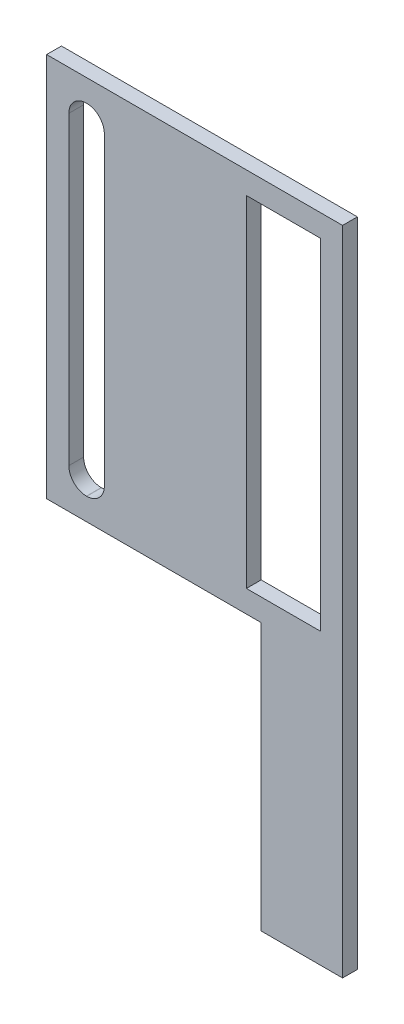
SolidWorks part; units mm, degrees
ref_plane "Front Plane" through (0, 0, 0) normal (0, 0, 1) x (1, 0, 0)
ref_plane "Top Plane" through (0, 0, 0) normal (0, 1, 0) x (1, 0, 0)
ref_plane "Right Plane" through (0, 0, 0) normal (1, 0, 0) x (0, 0, -1)
sketch "Sketch1" plane through (0, 0, 0) normal (0, 0, 1) x (1, 0, 0)
  line L1 (2.75, -19.65) -> (-2.75, -19.65)
  line L2 (2.75, -19.65) -> (2.75, 19.65)
  line L3 (2.75, 19.65) -> (-2.75, 19.65)
  line L4 (-2.75, -19.65) -> (-2.75, 19.65)
  line L5 (2.75, -19.65) -> (-2.75, 19.65) construction
  line L6 (2.75, 19.65) -> (-2.75, -19.65) construction
  point P0 (0, 0)
  dimension "D1" = 39.3
  dimension "D2" = 5.5
extrude "Boss-Extrude1" add sketch "Sketch1" along normal blind 1
sketch "Sketch2" plane through (0, 0, 1) normal (0, 0, 1) x (1, 0, 0)
  line L0 (-2.75, 19.65) -> (-2.75, -19.65) construction
  line L1 (2.75, 19.65) -> (-2.75, 19.65) construction
  line L3 (-0.25, 15.9) -> (-2.75, 15.9)
  line L4 (-0.25, 15.9) -> (-0.25, 12.9)
  line L5 (-0.25, 12.9) -> (-2.75, 12.9)
  line L6 (-2.75, 15.9) -> (-2.75, 12.9)
  line L7 (-0.25, 9.9) -> (-2.75, 9.9)
  line L8 (-0.25, 9.9) -> (-0.25, 6.9)
  line L9 (-0.25, 6.9) -> (-2.75, 6.9)
  line L10 (-2.75, 9.9) -> (-2.75, 6.9)
  circle A0 centre (-0.25, 14.4) radius 1.5
  circle A1 centre (-0.25, 8.4) radius 1.5
  dimension "D1" = 3
  dimension "D5" = 3
  dimension "D2" = 2.5
  dimension "D3" = 5.25
  dimension "D4" = 2.5
  dimension "D6" = 11.25
  dimension "D7" = 3
  dimension "D8" = 3
sketch "Sketch3" plane through (0, 0, 1) normal (0, 0, 1) x (1, 0, 0)
  line L0 (2.75, -19.65) -> (2.75, 19.65) construction
  line L1 (2.75, -1.6) -> (-17.25, -1.6)
  line L2 (2.75, -1.6) -> (2.75, 24.4)
  line L3 (2.75, 24.4) -> (-17.25, 24.4)
  line L4 (-17.25, -1.6) -> (-17.25, 24.4)
  dimension "D1" = 0
  dimension "D2" = 10
  dimension "D3" = 10
  dimension "D4" = 20
extrude "Boss-Extrude5" add sketch "Sketch3" against normal up to surface (1 mm away) up to face at (0, 0, 0)
sketch "Sketch4" plane through (0, 0, 1) normal (0, 0, 1) x (1, 0, 0)
  line L0 (2.75, 24.4) -> (-17.25, 24.4) construction
  line L1 (-14.56, 22.9) -> (-14.54, 22.9)
  line L2 (-15.75, 21.71) -> (-15.75, 1.09)
  line L3 (-14.56, -0.1) -> (-14.54, -0.1)
  line L4 (-13.35, 21.71) -> (-13.35, 1.09)
  line L5 (-17.25, -1.6) -> (-2.75, -1.6) construction
  line L6 (-17.25, 24.4) -> (-17.25, -1.6) construction
  arc A0 (-15.75, 1.09) -> (-14.56, -0.1) centre (-14.56, 1.09) ccw
  arc A1 (-14.54, -0.1) -> (-13.35, 1.09) centre (-14.54, 1.09) ccw
  arc A2 (-14.54, 22.9) -> (-13.35, 21.71) centre (-14.54, 21.71) cw
  arc A3 (-14.56, 22.9) -> (-15.75, 21.71) centre (-14.56, 21.71) ccw
  point P16 (-13.35, 22.9)
  point P19 (-15.75, 22.9)
  dimension "D5" = 1.19
  dimension "D1" = 1.5
  dimension "D2" = 1.5
  dimension "D3" = 1.5
  dimension "D4" = 2.4
extrude "Cut-Extrude3" cut sketch "Sketch4" against normal blind 1
sketch "Sketch5" plane through (0, 0, 1) normal (0, 0, 1) x (1, 0, 0)
  line L1 (-3.75, 22.9) -> (1.25, 22.9)
  line L2 (-3.75, 22.9) -> (-3.75, -0.1)
  line L3 (-3.75, -0.1) -> (1.25, -0.1)
  line L4 (1.25, 22.9) -> (1.25, -0.1)
  line L5 (-14.54, 22.9) -> (-14.56, 22.9) construction
  line L6 (-14.56, -0.1) -> (-14.54, -0.1) construction
  line L7 (2.75, -19.65) -> (2.75, 24.4) construction
  dimension "D1" = 5
  dimension "D2" = 0
  dimension "D3" = 0
  dimension "D4" = 1.5
extrude "Cut-Extrude4" cut sketch "Sketch5" against normal blind 1
